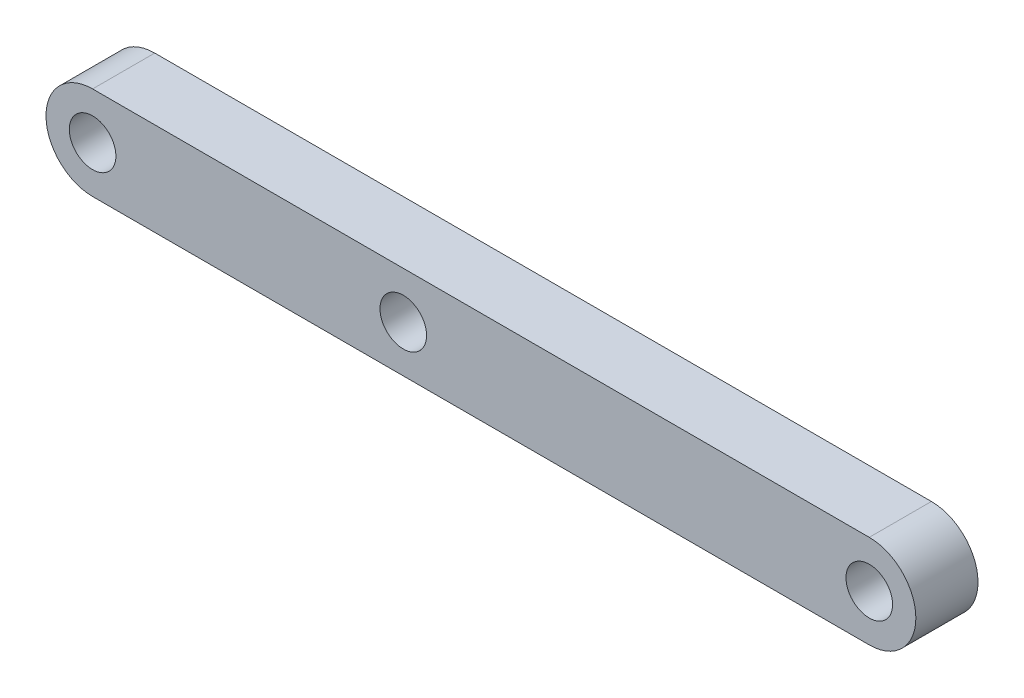
SolidWorks part; units mm, degrees
ref_plane "Front Plane" through (0, 0, 0) normal (0, 0, 1) x (1, 0, 0)
ref_plane "Top Plane" through (0, 0, 0) normal (0, 1, 0) x (1, 0, 0)
ref_plane "Right Plane" through (0, 0, 0) normal (1, 0, 0) x (0, 0, -1)
sketch "Sketch1" plane through (0, 0, 0) normal (0, 0, 1) x (1, 0, 0)
  line L0 (-25, 0) -> (25, 0) construction
  line L1 (-25, 3) -> (25, 3)
  line L2 (-25, -3) -> (25, -3)
  arc A0 (-25, 3) -> (-25, -3) centre (-25, 0) ccw
  arc A1 (25, -3) -> (25, 3) centre (25, 0) ccw
  circle A2 centre (-25, 0) radius 1.5
  circle A3 centre (25, 0) radius 1.5
  circle A4 centre (-5, 0) radius 1.5
  point P2 (0, 0)
  point P14 (20.5711, 0)
  dimension "D1" = 3
  dimension "D2" = 20
  dimension "D4" = 3
  dimension "D3" = 50
extrude "Boss-Extrude1" add sketch "Sketch1" along normal blind 4
